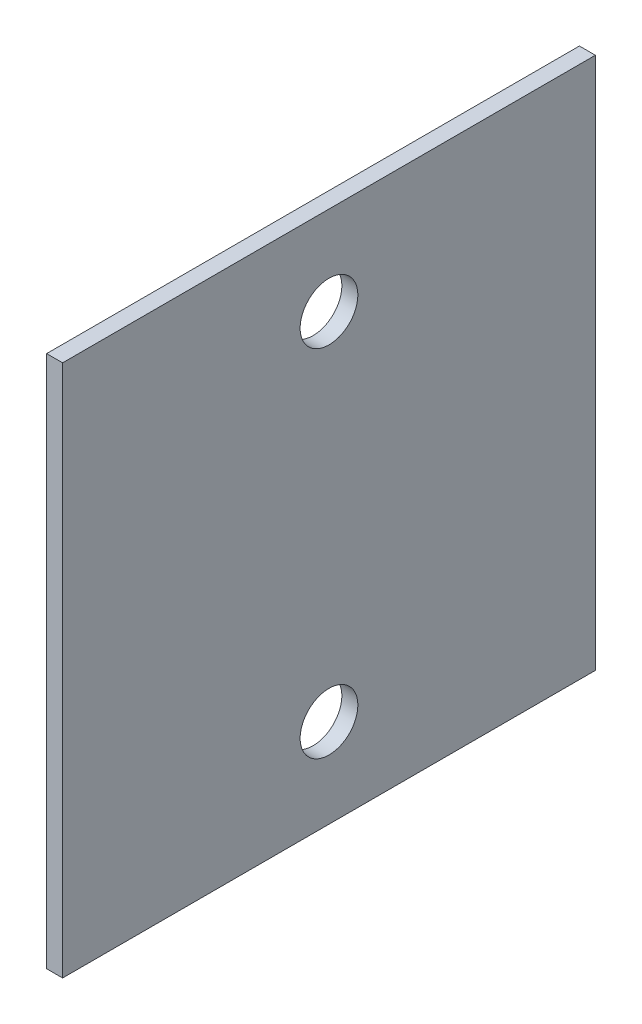
SolidWorks part; units mm, degrees
ref_plane "Front" through (0, 0, 0) normal (0, 0, 1) x (1, 0, 0)
ref_plane "Top" through (0, 0, 0) normal (0, 1, 0) x (1, 0, 0)
ref_plane "Right" through (0, 0, 0) normal (1, 0, 0) x (0, 0, -1)
sketch "Sketch1" plane through (0, 0, 0) normal (1, 0, 0) x (0, 0, -1)
  line L0 (7.1525, 0) -> (-66.3128, 0) construction
  line L1 (0, -30) -> (-60, -30)
  line L2 (0, -30) -> (0, 30)
  line L3 (0, 30) -> (-60, 30)
  line L4 (-60, -30) -> (-60, 30)
  dimension "D1" = 60
extrude "Boss-Extrude1" add sketch "Sketch1" along normal blind 1.8
hole_wizard "Ø6.5 (6.5) Diameter Hole1" positions "Sketch3" profile "Sketch2" hole size "Ø6.5" standard "ISO" end condition through all
sketch "Sketch3" plane through (1.8, 0, 0) normal (1, 0, 0) x (0, 0, -1)
  line L0 (0, 0) -> (-60, 0) construction
  line L1 (0, -30) -> (0, 30) construction
  line L2 (-60, 30) -> (-60, -30) construction
  point P0 (-30, -20)
  point P1 (-30, 20)
  dimension "D1" = 30
  dimension "D2" = 40
sketch "Sketch2" plane through (1.8, -20, 30) normal (0, 1, 0) x (0, 0, -1)
  line L0 (0, 0) -> (0, 1.8)
  line L1 (0, 1.8) -> (3.25, 1.8)
  line L2 (3.25, 1.8) -> (3.25, 0)
  line L5 (3.25, 0) -> (0, 0)
  line L11 (0, -6.35) -> (0, 107.95) construction
  dimension "Thru Hole Dia." = 6.5
  dimension "Thru Hole Depth" = 1.8
